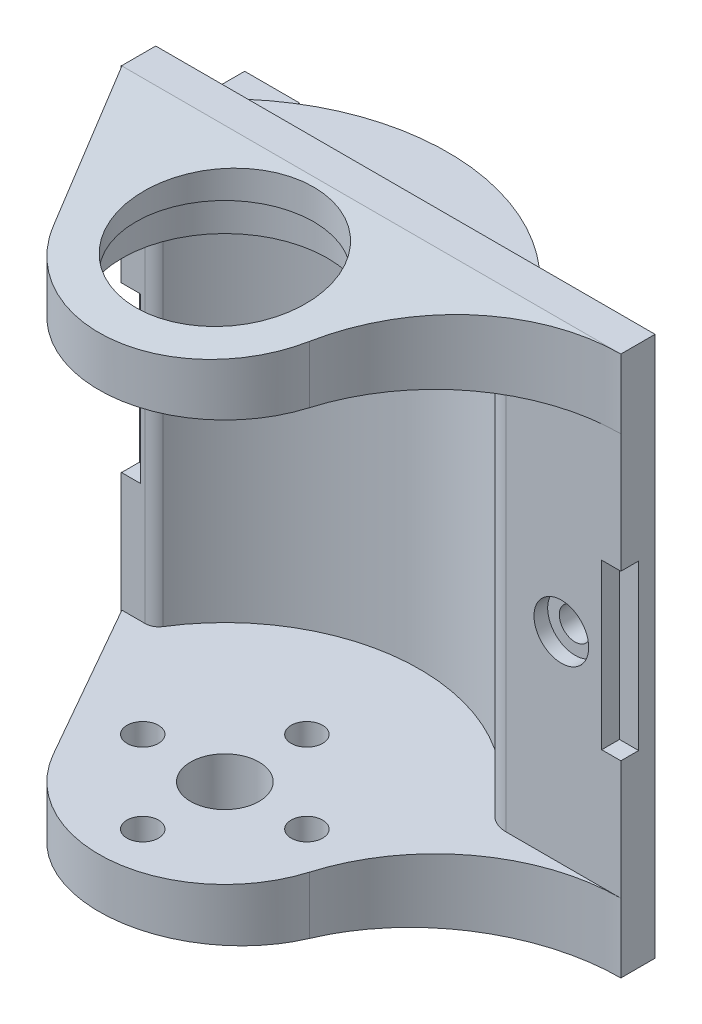
SolidWorks part; units mm, degrees
ref_plane "前视基准面" through (0, 0, 0) normal (0, 0, 1) x (1, 0, 0)
ref_plane "上视基准面" through (0, 0, 0) normal (0, 1, 0) x (1, 0, 0)
ref_plane "右视基准面" through (0, 0, 0) normal (1, 0, 0) x (0, 0, -1)
sketch "草图1" plane through (0, 0, 0) normal (0, 1, 0) x (1, 0, 0)
  circle A1 centre (0, 0) radius 16.3
  dimension "D1" = 32.6
extrude "凸台-拉伸1" add sketch "草图1" along normal mid plane 39.5
sketch "草图2" plane through (0, -19.75, 0) normal (0, -1, 0) x (1, 0, 0)
  line L1 (-14.65, -7.1) -> (21.85, -7.1)
  line L2 (-14.65, -7.1) -> (-14.65, -9.6)
  line L3 (-14.65, -9.6) -> (21.85, -9.6)
  line L4 (21.85, -7.1) -> (21.85, -9.6)
  dimension "D1" = 2.5
  dimension "D2" = 9.6
  dimension "D3" = 36.5
  dimension "D4" = 14.65
extrude "凸台-拉伸2" add sketch "草图2" against normal through all
sketch "草图3" plane through (0, -19.75, 0) normal (0, -1, 0) x (1, 0, 0)
  line L1 (21.85, -7.1) -> (-22.9944, -7.1)
  line L2 (21.85, -7.1) -> (21.85, 18.4067)
  line L3 (21.85, 18.4067) -> (-22.9944, 18.4067)
  line L4 (-22.9944, -7.1) -> (-22.9944, 18.4067)
extrude "切除-拉伸1" cut sketch "草图3" against normal blind 50
sketch "草图4" plane through (0, -19.75, 0) normal (0, -1, 0) x (1, 0, 0)
  line L0 (-14.65, -7.1462) -> (-7.9965, 4.5492)
  line L1 (21.85, -7.1) -> (21.85, 7.9567) construction
  line L2 (-14.65, -7.1462) -> (21.85, -7.1)
  arc A0 (8.8187, 2.6213) -> (-7.9965, 4.5492) centre (0, 0) ccw
  arc A1 (8.8187, 2.6213) -> (21.85, -7.1) centre (21.85, 6.4949) ccw
  dimension "D1" = 18.4
extrude "凸台-拉伸3" add sketch "草图4" against normal blind 5.05
mirror "镜向1" about plane through (0, 0, 0) normal (0, 1, 0) of "凸台-拉伸3"
sketch "草图5" plane through (0, -14.7, 0) normal (0, 1, 0) x (1, 0, 0)
  circle A0 centre (0, 0) radius 14.25
  dimension "D1" = 28.5
extrude "切除-拉伸2" cut sketch "草图5" along normal up to surface (29.4 mm away) up to face at (1.768, 14.7, -0.9093)
sketch "草图6" plane through (0, -14.7, 0) normal (0, 1, 0) x (1, 0, 0)
  circle A0 centre (0, 0) radius 2.5
  dimension "D1" = 5
extrude "切除-拉伸3" cut sketch "草图6" against normal through all
sketch "草图9" plane through (0, 19.75, 0) normal (0, 1, 0) x (1, 0, 0)
  circle A0 centre (0, 0) radius 7.5
  dimension "D1" = 15
extrude "切除-拉伸6" cut sketch "草图9" against normal up to next
sketch "草图12" plane through (0, 0, -7.1) normal (0, 0, 1) x (1, 0, 0)
  line L0 (0, 0) -> (30.0134, 0) construction
  line L1 (21.85, 14.7) -> (21.85, -14.7) construction
  circle A0 centre (17.5, 0) radius 1.15
  dimension "D1" = 2.3
  dimension "D2" = 4.35
extrude "切除-拉伸9" cut sketch "草图12" against normal through all
sketch "草图13" plane through (0, 0, -7.1) normal (0, 0, 1) x (1, 0, 0)
  circle A0 centre (17.5, 0) radius 2
  dimension "D1" = 4
extrude "切除-拉伸10" cut sketch "草图13" against normal blind 1
sketch "草图14" plane through (0, 0, -7.1) normal (0, 0, 1) x (1, 0, 0)
  line L0 (21.85, 14.7) -> (21.85, -14.7) construction
  line L1 (20.45, -6) -> (23.25, -6)
  line L2 (20.45, -6) -> (20.45, 6)
  line L3 (20.45, 6) -> (23.25, 6)
  line L4 (23.25, -6) -> (23.25, 6)
  line L5 (20.45, -6) -> (23.25, 6) construction
  line L6 (20.45, 6) -> (23.25, -6) construction
  point P0 (21.85, 0)
  dimension "12" = 12
  dimension "D2" = 2.8
extrude "切除-拉伸11" cut sketch "草图14" against normal blind 1.3
sketch "草图15" plane through (0, 0, -7.1) normal (0, 0, 1) x (1, 0, 0)
  line L0 (0, 0) -> (-23.1213, 0) construction
  line L1 (-14.6724, -19.75) -> (-14.6724, 19.75) construction
  line L2 (-16.0724, -6) -> (-13.2724, -6)
  line L3 (-16.0724, -6) -> (-16.0724, 6)
  line L4 (-16.0724, 6) -> (-13.2724, 6)
  line L5 (-13.2724, -6) -> (-13.2724, 6)
  line L6 (-16.0724, -6) -> (-13.2724, 6) construction
  line L7 (-16.0724, 6) -> (-13.2724, -6) construction
  point P3 (-14.6724, 0)
  dimension "D1" = 12
  dimension "D2" = 2.8
extrude "切除-拉伸12" cut sketch "草图15" against normal blind 1.3
ref_plane "基准面1" through (0, 0, -15.1) normal (0, 0, -1) x (-1, 0, 0)
sketch "草图16" plane through (0, 0, -15.1) normal (0, 0, -1) x (-1, 0, 0)
  line L0 (14.65, 19.75) -> (14.65, -19.75) construction
  line L1 (9.65, 10.9) -> (13.65, 10.9)
  line L2 (9.65, 10.9) -> (9.65, 15.9)
  line L3 (9.65, 15.9) -> (13.65, 15.9)
  line L4 (13.65, 10.9) -> (13.65, 15.9)
  line L5 (9.65, 10.9) -> (13.65, 15.9) construction
  line L6 (9.65, 15.9) -> (13.65, 10.9) construction
  line L7 (0, 0) -> (27.535, 0) construction
  point P0 (11.65, 13.4)
  dimension "D1" = 1
  dimension "D2" = 10.9
  dimension "D3" = 5
  dimension "D4" = 4
extrude "凸台-拉伸5" add sketch "草图16" against normal up to surface (1.9635 mm away)
mirror "镜向4" about plane through (0, 0, 0) normal (0, 1, 0) of "凸台-拉伸5"
sketch "草图17" plane through (0, 0, -15.1) normal (0, 0, -1) x (-1, 0, 0)
  line L0 (11.65, 15.9) -> (11.65, 12.48) construction
  line L1 (13.65, 15.9) -> (9.65, 15.9) construction
  line L2 (13.65, 13.4) -> (11.1035, 13.4) construction
  line L3 (13.65, 10.9) -> (13.65, 15.9) construction
  line L5 (11.15, 12.4) -> (12.15, 12.4)
  line L6 (11.15, 12.4) -> (11.15, 14.4)
  line L7 (11.15, 14.4) -> (12.15, 14.4)
  line L8 (12.15, 12.4) -> (12.15, 14.4)
  line L9 (11.15, 12.4) -> (12.15, 14.4) construction
  line L10 (11.15, 14.4) -> (12.15, 12.4) construction
  point P8 (11.65, 13.4)
  dimension "D1" = 2
  dimension "D2" = 1
extrude "切除-拉伸13" cut sketch "草图17" against normal blind 2.5
mirror "镜向5" about plane through (0, 0, 0) normal (0, 1, 0) of "切除-拉伸13"
sketch "草图19" plane through (0, 19.75, 0) normal (0, 1, 0) x (1, 0, 0)
  circle A1 centre (0, 0) radius 6.5
  circle A2 centre (0, 0) radius 8.519
  dimension "D1" = 13
extrude "凸台-拉伸6" add sketch "草图19" against normal blind 2.25
sketch "草图20" plane through (0, -19.75, 0) normal (0, -1, 0) x (1, 0, 0)
  circle A0 centre (0, 6) radius 1.15
  dimension "D1" = 2.3
  dimension "D2" = 6
extrude "切除-拉伸18" cut sketch "草图20" against normal up to next
pattern_circular "阵列(圆周)1" count 4 over 360 about axis through (0, 0, 0) along (0, 1, 0) of "切除-拉伸18"
sketch "草图7" plane through (-14.65, 0, 0) normal (-1, 0, 0) x (0, 0, 1)
  line L0 (-7.1, 19.75) -> (9.2, 18.3239)
  line L1 (9.2, 14.7) -> (9.2, 19.75) construction
  line L2 (9.2, 18.3239) -> (9.2, 19.75)
  line L3 (9.2, 19.75) -> (-7.1, 19.75)
  dimension "D1" = 5
extrude "切除-拉伸8" cut sketch "草图7" against normal through all
mirror "镜向3" about plane through (0, 0, 0) normal (0, 1, 0) of "切除-拉伸8"
sketch "草图18" plane through (0, 0, -9.6) normal (0, 0, -1) x (-1, 0, 0)
  line L0 (-13.1731, 19.75) -> (-13.1731, -19.75) construction
  line L1 (13.1731, 19.75) -> (-13.1731, 19.75)
  line L2 (13.1731, 19.75) -> (13.1731, 17)
  line L3 (13.1731, 17) -> (-13.1731, 17)
  line L4 (-13.1731, 19.75) -> (-13.1731, 17)
  dimension "D1" = 2.75
extrude "切除-拉伸16" cut sketch "草图18" along normal blind 12.5
mirror "镜向6" about plane through (0, 0, 0) normal (0, 1, 0) of "切除-拉伸16"
fillet "圆角1" radius 2 1 edges at (12.3553, 0, -7.1)
fillet "圆角2" radius 1 1 edges at (-12.3553, 0, -7.1)
sketch "草图21" plane through (0, -19.75, 0) normal (0, -1, 0) x (1, 0, 0)
  circle A0 centre (0, 6) radius 2.1
  circle A1 centre (-6, 0) radius 2.1
  circle A2 centre (6, 0) radius 2.1
  circle A3 centre (0, -6) radius 2.1
  dimension "D1" = 4.2
extrude "切除-拉伸19" cut sketch "草图21" against normal blind 2.5
